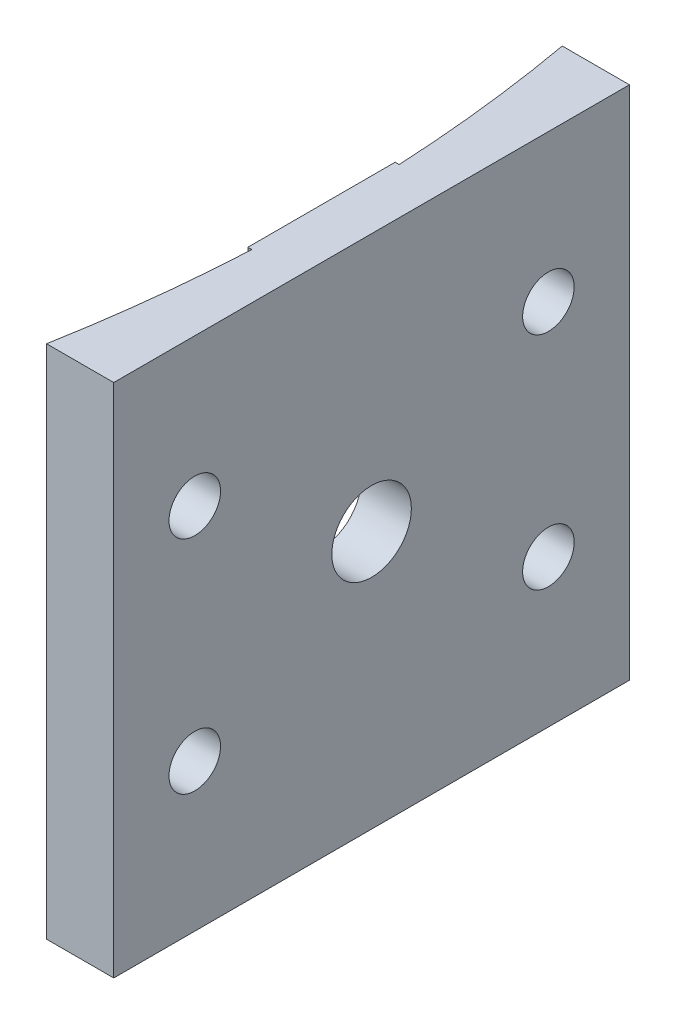
SolidWorks part; units mm, degrees
ref_plane "Спереди" through (0, 0, 0) normal (0, 0, 1) x (1, 0, 0)
ref_plane "Сверху" through (0, 0, 0) normal (0, 1, 0) x (1, 0, 0)
ref_plane "Справа" through (0, 0, 0) normal (1, 0, 0) x (0, 0, -1)
sketch "Эскиз1" plane through (0, 0, 0) normal (0, 1, 0) x (1, 0, 0)
  line L0 (-4.559, 17.5) -> (-4.559, -17.5) construction
  line L1 (-102, 0) -> (-3, 0) construction
  line L2 (-4.559, 17.5) -> (0, 17.5)
  line L3 (0, 17.5) -> (0, -17.5)
  line L4 (0, -17.5) -> (-4.559, -17.5)
  line L5 (-4.559, -17.5) -> (-102, 0) construction
  line L6 (-102, 0) -> (-4.559, 17.5) construction
  arc A0 (-4.559, 17.5) -> (-4.559, -17.5) centre (-102, 0) cw
  dimension "D1" = 99
  dimension "D2" = 35
  dimension "D3" = 3
  dimension "D4" = 4.559
extrude "Бобышка-Вытянуть1" add sketch "Эскиз1" along normal blind 35
sketch "Эскиз2" plane through (0, 0, 0) normal (1, 0, 0) x (0, 0, -1)
  line L0 (-17.5, 0) -> (17.5, 0) construction
  line L1 (-12, 25) -> (12, 25) construction
  line L2 (-12, 25) -> (-12, 10) construction
  line L3 (-12, 10) -> (12, 10) construction
  line L4 (12, 25) -> (12, 10) construction
  line L5 (-12, 25) -> (12, 10) construction
  line L6 (-12, 10) -> (12, 25) construction
  line L7 (0, 10) -> (0, 0) construction
  circle A0 centre (-12, 25) radius 1.75
  circle A1 centre (12, 25) radius 1.75
  circle A2 centre (12, 10) radius 1.75
  circle A3 centre (-12, 10) radius 1.75
  point P0 (0, 17.5)
  dimension "D4" = 3.5
  dimension "D5" = 3.5
  dimension "D6" = 3.5
  dimension "D7" = 3.5
  dimension "D1" = 10
  dimension "D2" = 15
  dimension "D3" = 24
extrude "Вырез-Вытянуть1" cut sketch "Эскиз2" against normal through all
sketch "Эскиз3" plane through (0, 0, 0) normal (0, -1, 0) x (1, 0, 0)
  line L1 (-3.4, 5) -> (-2.6, 5)
  line L2 (-3.4, 5) -> (-3.4, -5)
  line L3 (-3.4, -5) -> (-2.6, -5)
  line L4 (-2.6, 5) -> (-2.6, -5)
  line L5 (-3.4, 5) -> (-2.6, -5) construction
  line L6 (-3.4, -5) -> (-2.6, 5) construction
  arc A0 (-4.559, -17.5) -> (-4.559, 17.5) centre (-102, 0) ccw construction
  point P0 (-3, 0)
  dimension "D1" = 10
  dimension "D2" = 0.8
extrude "Бобышка-Вытянуть2" add sketch "Эскиз3" against normal up to surface (35 mm away) up to face at (-1.8897, 35, 0)
sketch "Эскиз4" plane through (0, 0, 0) normal (1, 0, 0) x (0, 0, -1)
  line L0 (-17.5, 0) -> (17.5, 35) construction
  line L1 (17.5, 35) -> (-17.5, 35) construction
  line L2 (-17.5, 35) -> (17.5, 0) construction
  circle A0 centre (0, 17.5) radius 2.7
  dimension "D1" = 5.4
extrude "Вырез-Вытянуть2" cut sketch "Эскиз4" against normal through all
